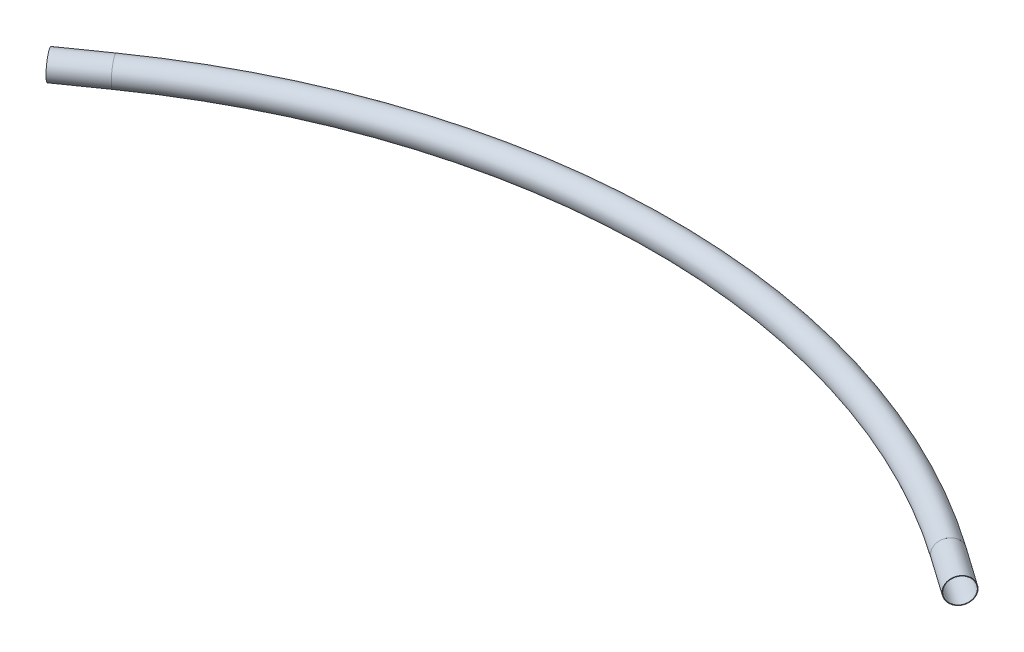
SolidWorks part; units mm, degrees
ref_plane "Front Plane" through (0, 0, 0) normal (0, 0, 1) x (1, 0, 0)
ref_plane "Top Plane" through (0, 0, 0) normal (0, 1, 0) x (1, 0, 0)
ref_plane "Right Plane" through (0, 0, 0) normal (1, 0, 0) x (0, 0, -1)
sketch "Pipe_Definition" plane through (0, 0, 0) normal (0, 1, 0) x (1, 0, 0)
  line L0 (0, 0) -> (0, 857.25) construction
  line L1 (-2711.45, 0) -> (2711.45, 0) construction
  line L6 (-2711.45, 0) -> (-2960.8536, -175.2166)
  line L10 (2711.45, 0) -> (2960.8536, -175.2166)
  arc A1 (2711.45, 0) -> (-2711.45, 0) centre (0, -3859.483) ccw
  dimension "D1" = 304.8
  dimension "D3" = 5422.9
  dimension "D4" = 2843.7367
  dimension "D2" = 857.25
other "Structural Member1"
ref_plane "Plane1" through (2711.45, 0, 0) normal (-0.8183, 0, -0.5749) x (-0.5749, 0, 0.8183)
sketch "Sketch12" plane through (2711.45, 0, 0) normal (-0.8183, 0, -0.5749) x (-0.5749, 0, 0.8183)
  circle A0 centre (0, 0) radius 84.1375
  circle A1 centre (0, 0) radius 80.7339
  point P4 (0, 0)
  dimension "D1" = 168.275
  dimension "D2" = 161.4678
equation "\"D2@Sketch12\" = \"D1@Sketch12\" - .134*2"
